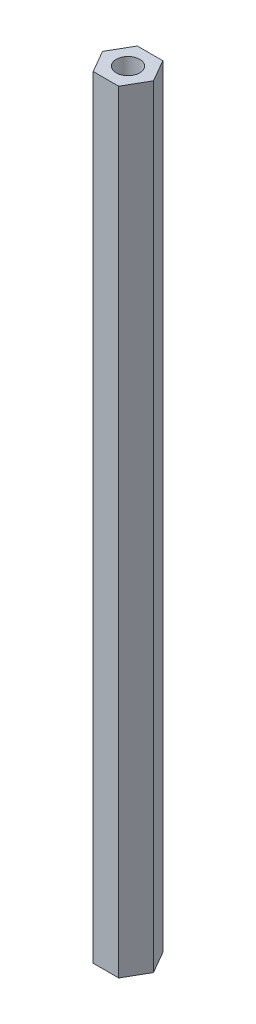
SolidWorks part; units mm, degrees
ref_plane "前视基准面" through (0, 0, 0) normal (0, 0, 1) x (1, 0, 0)
ref_plane "上视基准面" through (0, 0, 0) normal (0, 1, 0) x (1, 0, 0)
ref_plane "右视基准面" through (0, 0, 0) normal (1, 0, 0) x (0, 0, -1)
sketch "草图1" plane through (0, 0, 0) normal (0, 1, 0) x (1, 0, 0)
  line L0 (0, 0) -> (3.4641, 0) construction
  line L1 (3.4641, 0) -> (1.7321, 3)
  line L2 (1.7321, 3) -> (-1.7321, 3)
  line L3 (-1.7321, 3) -> (-3.4641, 0)
  line L4 (-3.4641, 0) -> (-1.7321, -3)
  line L5 (-1.7321, -3) -> (1.7321, -3)
  line L6 (1.7321, -3) -> (3.4641, 0)
  circle A0 centre (0, 0) radius 1.6
  circle A1 centre (0, 0) radius 3 construction
  dimension "D1" = 3.2
  dimension "D2" = 6
extrude "凸台-拉伸1" add sketch "草图1" along normal blind 105
cosmetic thread "装饰螺纹线1" parameters "D1"=25, "D2"=9.6
cosmetic thread "装饰螺纹线2" parameters "D1"=25, "D2"=9.6
